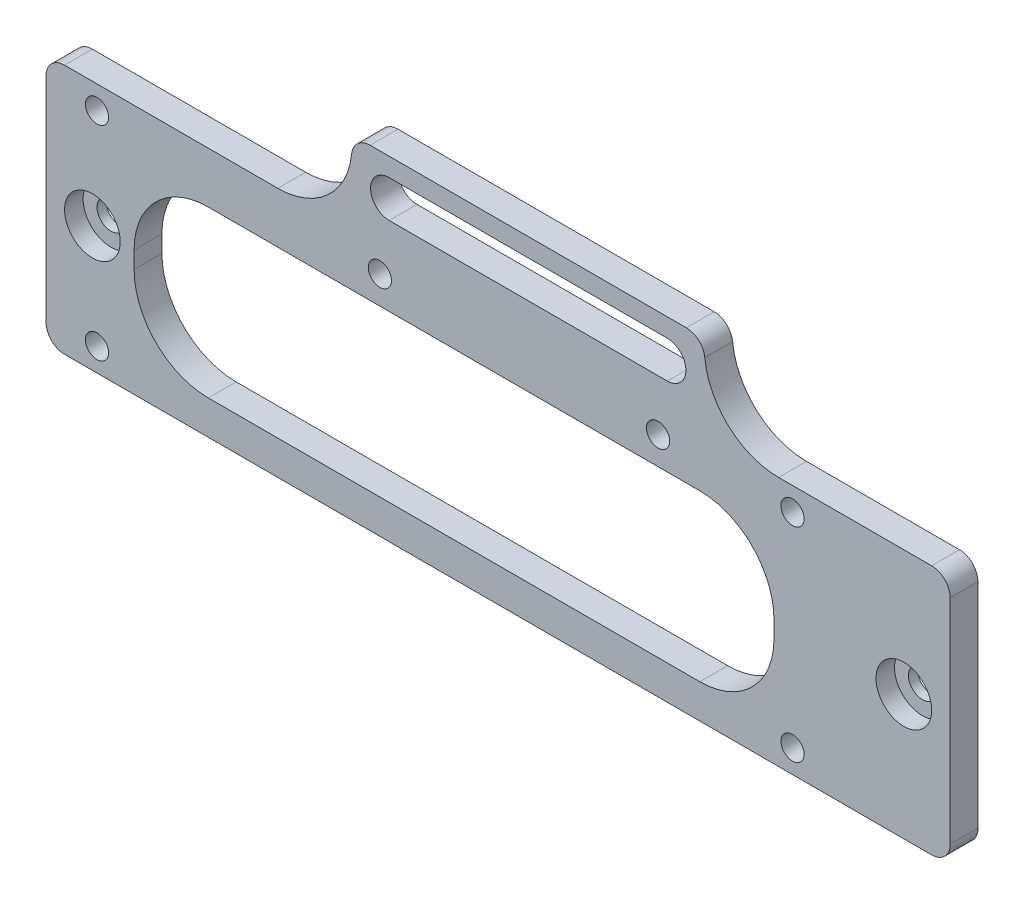
SolidWorks part; units mm, degrees
material "3.0205 (EN-AW 1200)"
ref_plane "前视基准面" through (0, 0, 0) normal (0, 0, 1) x (1, 0, 0)
ref_plane "上视基准面" through (0, 0, 0) normal (0, 1, 0) x (1, 0, 0)
ref_plane "右视基准面" through (0, 0, 0) normal (1, 0, 0) x (0, 0, -1)
other "Configuration Table"
sketch "草图3" plane through (0, 0, 0) normal (0, 0, 1) x (1, 0, 0)
  line L2 (-48.75, 13.5) -> (-48.75, -13.5)
  line L3 (-48.75, -13.5) -> (48.75, -13.5)
  line L4 (48.75, 13.5) -> (48.75, -13.5)
  line L5 (-48.75, 13.5) -> (48.75, -13.5) construction
  line L6 (-48.75, -13.5) -> (48.75, 13.5) construction
  line L16 (-48.75, 13.5) -> (48.75, 13.5)
  point P0 (0, 0)
  dimension "D1" = 97.5
  dimension "D2" = 27
extrude "凸台-拉伸1" add sketch "草图3" along normal blind 3
sketch "草图4" plane through (0, 0, 3) normal (0, 0, 1) x (1, 0, 0)
  line L0 (-48.75, 13.5) -> (-48.75, -13.5) construction
  line L2 (48.75, 13.5) -> (-48.75, 13.5) construction
  circle A0 centre (-43.25, 11) radius 1.25
  circle A1 centre (-43.25, -11) radius 1.25
  circle A2 centre (31.75, 11) radius 1.25
  circle A3 centre (31.75, -11) radius 1.25
  circle A4 centre (17.25, 11) radius 1.25
  circle A5 centre (-12.75, 11) radius 1.25
  dimension "D1" = 2.5
  dimension "D5" = 5.5
  dimension "D6" = 2.5
  dimension "D7" = 22
  dimension "D8" = 75
  dimension "D11" = 14.5
  dimension "D12" = 30
extrude "切除-拉伸1" cut sketch "草图4" against normal through all
sketch "草图7" plane through (0, 0, 0) normal (0, 0, -1) x (-1, 0, 0)
  line L0 (48.75, 13.5) -> (48.75, -13.5) construction
  line L1 (48.75, -3.5) -> (44.75, -3.5)
  line L2 (48.75, -3.5) -> (48.75, 4.5)
  line L3 (48.75, 4.5) -> (44.75, 4.5)
  line L4 (44.75, -3.5) -> (44.75, 4.5)
  line L5 (-48.75, -13.5) -> (-48.75, 13.5) construction
  line L6 (-48.75, -3.5) -> (-44.75, -3.5)
  line L7 (-48.75, -3.5) -> (-48.75, 4.5)
  line L8 (-48.75, 4.5) -> (-44.75, 4.5)
  line L9 (-44.75, -3.5) -> (-44.75, 4.5)
  line L10 (48.75, -13.5) -> (-48.75, -13.5) construction
  line L11 (48.75, -13.5) -> (-48.75, -13.5) construction
  dimension "D1" = 4
  dimension "D2" = 4
  dimension "D3" = 8
  dimension "D4" = 8
  dimension "D5" = 10
  dimension "D6" = 10
extrude "凸台-拉伸2" add sketch "草图7" along normal blind 5
sketch "草图8" plane through (0, 0, 3) normal (0, 0, 1) x (1, 0, 0)
  line L0 (-11.75, 18.5) -> (18.25, 18.5) construction
  line L1 (48.75, 13.5) -> (-48.75, 13.5) construction
  line L2 (-48.75, 13.5) -> (-48.75, -13.5) construction
  line L3 (-11.75, 20.5) -> (18.25, 20.5)
  line L4 (-15.75, 13.5) -> (22.25, 13.5)
  line L5 (-15.75, 13.5) -> (-15.75, 22.5)
  line L6 (-15.75, 22.5) -> (22.25, 22.5)
  line L7 (22.25, 13.5) -> (22.25, 22.5)
  line L8 (-11.75, 16.5) -> (18.25, 16.5)
  arc A0 (-11.75, 20.5) -> (-11.75, 16.5) centre (-11.75, 18.5) ccw
  arc A1 (18.25, 16.5) -> (18.25, 20.5) centre (18.25, 18.5) ccw
  point P10 (3.25, 18.5)
  dimension "D4" = 2
  dimension "D1" = 38
  dimension "D2" = 33
  dimension "D3" = 9
  dimension "D5" = 5
  dimension "D6" = 4
  dimension "D7" = 4
extrude "凸台-拉伸3" add sketch "草图8" against normal up to surface (3 mm away) up to face at (-11.5, 11, 0)
fillet "圆角3" radius 8 2 edges at (22.25, 13.5, 1.5) (-15.75, 13.5, 1.5)
fillet "圆角4" radius 2 2 edges at (-15.75, 22.5, 1.5) (22.25, 22.5, 1.5)
sketch "草图9" plane through (0, 0, -5) normal (0, 0, -1) x (-1, 0, 0)
  line L4 (-48.75, 4.5) -> (-48.75, -3.5)
  line L5 (-48.75, -3.5) -> (-44.75, -3.5)
  line L6 (-44.75, -3.5) -> (-44.75, 4.5)
  line L7 (-44.75, 4.5) -> (-48.75, 4.5)
  line L8 (-48.75, 4.5) -> (-48.75, -3.5)
  line L9 (-48.75, -3.5) -> (-44.75, -3.5)
  line L10 (-44.75, -3.5) -> (-44.75, 4.5)
  line L11 (-44.75, 4.5) -> (-48.75, 4.5)
  line L12 (48.75, -3.5) -> (48.75, 4.5)
  line L13 (48.75, 4.5) -> (44.75, 4.5)
  line L14 (44.75, 4.5) -> (44.75, -3.5)
  line L15 (44.75, -3.5) -> (48.75, -3.5)
  line L16 (48.75, -3.5) -> (48.75, 4.5)
  line L17 (48.75, 4.5) -> (44.75, 4.5)
  line L18 (44.75, 4.5) -> (44.75, -3.5)
  line L19 (44.75, -3.5) -> (48.75, -3.5)
  dimension "D1" = 0
  dimension "D2" = 0
extrude "切除-拉伸4" cut sketch "草图9" against normal up to surface (5 mm away) and the other way through all up to face at (-11.5, 11, 0)
sketch "草图13" plane through (0, 0, 0) normal (0, 0, -1) x (-1, 0, 0)
  line L0 (-48.75, -13.5) -> (-48.75, 13.5) construction
  line L1 (48.75, 13.5) -> (48.75, -13.5) construction
  circle A0 centre (-43.75, 0) radius 1.5
  circle A2 centre (43.75, 0) radius 1.5
  point P8 (-48.75, 0)
  dimension "D1" = 3
  dimension "D2" = 3
  dimension "D3" = 5
  dimension "D4" = 5
extrude "切除-拉伸7" cut sketch "草图13" against normal through all
sketch "草图16" plane through (0, 0, 3) normal (0, 0, 1) x (1, 0, 0)
  circle A0 centre (-43.75, 0) radius 3
  circle A1 centre (43.75, 0) radius 3
  dimension "D1" = 6
extrude "切除-拉伸9" cut sketch "草图16" against normal blind 2
sketch "草图17" plane through (0, 0, 0) normal (0, 0, -1) x (-1, 0, 0)
  line L0 (-31.75, 11) -> (43.25, -11) construction
  line L1 (43.25, 11) -> (-31.75, -11) construction
  line L3 (39.25, -8) -> (-27.75, -8) construction
  line L4 (39.25, -8) -> (39.25, 8)
  line L5 (39.25, 8) -> (-27.75, 8)
  line L6 (-27.75, -8) -> (-27.75, 8) construction
  line L7 (39.25, -8) -> (-27.75, 8) construction
  line L8 (39.25, 8) -> (-27.75, -8) construction
  line L9 (-27.75, -8) -> (39.25, -8) construction
  line L10 (-27.75, -8) -> (-27.75, -9.8267) construction
  line L11 (-27.75, -9.8267) -> (39.25, -9.8267)
  line L12 (39.25, -8) -> (39.25, -9.8267)
  line L13 (-27.75, 8) -> (-29.75, 8)
  line L14 (-27.75, 8) -> (-27.75, -9.8267) construction
  line L15 (-27.75, -9.8267) -> (-29.75, -9.8267)
  line L16 (-29.75, 8) -> (-29.75, -9.8267)
  circle A0 centre (-31.75, 11) radius 1.25 construction
  circle A1 centre (-17.25, 11) radius 1.25 construction
  point P8 (5.75, 0)
  dimension "D2" = 3
  dimension "D1" = 4
  dimension "D3" = 2
extrude "切除-拉伸10" cut sketch "草图17" against normal blind 10
fillet "圆角5" radius 8 4 edges at (-39.25, 8, 1.5) (-39.25, -9.8267, 1.5) (29.75, -9.8267, 1.5) (29.75, 8, 1.5)
fillet "圆角6" radius 2 4 edges at (-48.75, 13.5, 1.5) (-48.75, -13.5, 1.5) (48.75, -13.5, 1.5) (48.75, 13.5, 1.5)
hole_wizard "M3 螺纹孔1" positions "3D草图1" profile "草图18" tap size "M3" standard "GB"
sketch3d "3D草图1"
  line L0 (-43.25, 11, 0) -> (-43.25, 11, 3) construction
  line L1 (-43.25, -11, 0) -> (-43.25, -11, 3) construction
  line L2 (-12.75, 11, 0) -> (-12.75, 11, 3) construction
  line L3 (17.25, 11, 0) -> (17.25, 11, 3) construction
  line L4 (31.75, 11, 0) -> (31.75, 11, 3) construction
  line L5 (31.75, -11, 0) -> (31.75, -11, 3) construction
  point P0 (-43.25, 11, 3)
  point P4 (-43.25, -11, 3)
  point P8 (-12.75, 11, 3)
  point P12 (17.25, 11, 3)
  point P16 (31.75, 11, 3)
  point P20 (31.75, -11, 3)
sketch "草图18" plane through (-43.25, 11, 3) normal (1, 0, 0) x (0, -1, 0)
  line L0 (0, 0) -> (0, 3.7511)
  line L1 (0, 3.7511) -> (1.25, 3)
  line L2 (1.25, 3) -> (1.25, 0)
  line L5 (1.25, 0) -> (0, 0)
  line L10 (0, 3.7511) -> (-1.25, 3) construction
  line L11 (0, -6.35) -> (0, 107.95) construction
  dimension "螺纹孔钻头直径" = 2.5
  dimension "螺纹孔钻头深度" = 3
  dimension "导头角度" = 118
cosmetic thread "孔螺纹线1" parameters "D1"=6, "D2"=3
cosmetic thread "孔螺纹线2" parameters "D1"=6, "D2"=3
cosmetic thread "孔螺纹线3" parameters "D1"=6, "D2"=3
cosmetic thread "孔螺纹线4" parameters "D1"=6, "D2"=3
cosmetic thread "孔螺纹线5" parameters "D1"=6, "D2"=3
cosmetic thread "孔螺纹线6" parameters "D1"=6, "D2"=3
